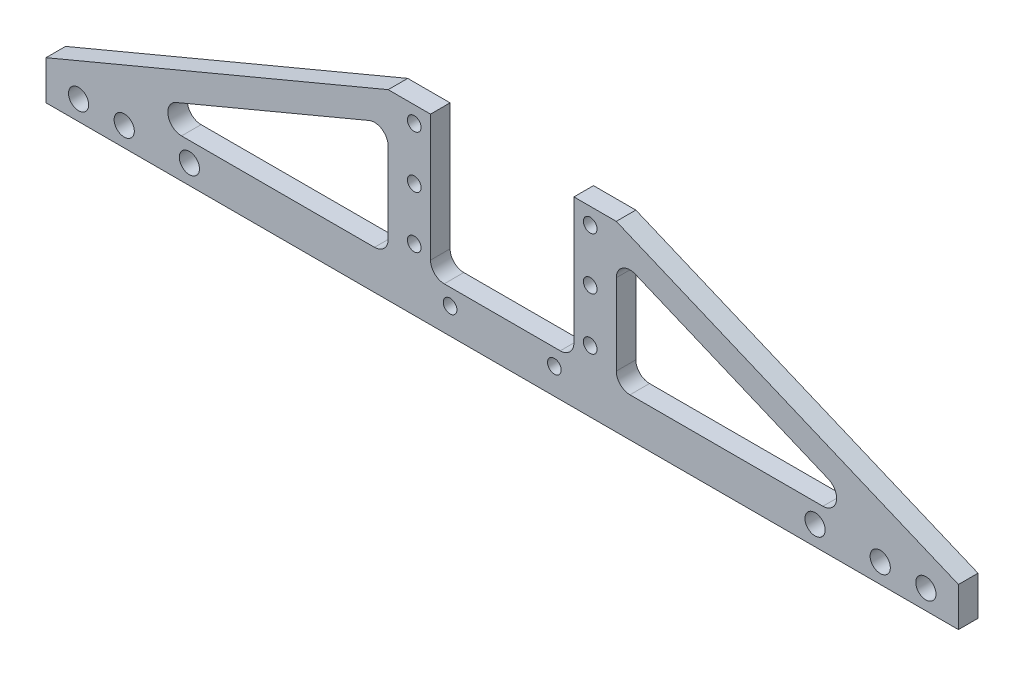
SolidWorks part; units mm, degrees
ref_plane "正面" through (0, 0, 0) normal (0, 0, 1) x (1, 0, 0)
ref_plane "平面" through (0, 0, 0) normal (0, 1, 0) x (1, 0, 0)
ref_plane "右側面" through (0, 0, 0) normal (1, 0, 0) x (0, 0, -1)
sketch "ｽｹｯﾁ1" plane through (0, 0, 0) normal (0, 0, 1) x (1, 0, 0)
  line L0 (-13.5, 21.5) -> (-13.5, 13.5) construction
  line L5 (-13.5, 13.5) -> (-13.5, 5.5) construction
  line L6 (-13.5, 5.5) -> (-13.5, 0) construction
  line L7 (-13.5, 0) -> (-8, 0) construction
  line L8 (-8, 0) -> (8, 0) construction
  line L9 (8, 0) -> (13.5, 0) construction
  line L10 (13.5, 0) -> (13.5, 5.5) construction
  line L11 (13.5, 5.5) -> (13.5, 13.5) construction
  line L12 (13.5, 13.5) -> (13.5, 21.5) construction
  line L13 (-11, 4.6) -> (-11, 24)
  line L14 (-11, 24) -> (-17.5, 24)
  line L15 (-17.5, 24) -> (-17.5, -4) construction
  line L16 (-17.5, -4) -> (17.5, -4)
  line L17 (17.5, -4) -> (17.5, 24) construction
  line L18 (17.5, 24) -> (11, 24)
  line L19 (11, 24) -> (11, 4.6)
  line L20 (8.9, 2.5) -> (-8.9, 2.5)
  line L21 (-17.5, 24) -> (-70, 2)
  line L22 (-70, -4) -> (-17.5, -4)
  line L23 (-17.5, 4.1) -> (-17.5, 16.5061)
  line L24 (-20.4116, 18.4429) -> (-50.017, 6.0368)
  line L25 (-49.2054, 2) -> (-19.6, 2)
  line L26 (-70, 2) -> (-70, -4)
  line L27 (-70, -1) -> (-65, -1) construction
  line L28 (-65, -1) -> (-65, -4) construction
  line L29 (0, -4) -> (0, 24) construction
  line L30 (70, -4) -> (17.5, -4)
  line L31 (70, 2) -> (70, -4)
  line L32 (17.5, 24) -> (70, 2)
  line L33 (20.4116, 18.4429) -> (50.017, 6.0368)
  line L34 (17.5, 4.1) -> (17.5, 16.5061)
  line L35 (49.2054, 2) -> (19.6, 2)
  circle A0 centre (-13.5, 5.5) radius 1.05
  circle A1 centre (-8, 0) radius 1.05
  circle A2 centre (8, 0) radius 1.05
  circle A3 centre (-13.5, 13.5) radius 1.05
  circle A4 centre (-13.5, 21.5) radius 1.05
  circle A5 centre (13.5, 21.5) radius 1.05
  circle A6 centre (13.5, 13.5) radius 1.05
  circle A7 centre (13.5, 5.5) radius 1.05
  arc A8 (-17.5, 4.1) -> (-19.6, 2) centre (-19.6, 4.1) cw
  arc A9 (-50.017, 6.0368) -> (-49.2054, 2) centre (-49.2054, 4.1) ccw
  arc A10 (-17.5, 16.5061) -> (-20.4116, 18.4429) centre (-19.6, 16.5061) ccw
  circle A11 centre (-65, -1) radius 1.55
  circle A12 centre (65, -1) radius 1.55
  arc A13 (17.5, 16.5061) -> (20.4116, 18.4429) centre (19.6, 16.5061) cw
  arc A14 (17.5, 4.1) -> (19.6, 2) centre (19.6, 4.1) ccw
  arc A15 (50.017, 6.0368) -> (49.2054, 2) centre (49.2054, 4.1) cw
  arc A16 (11, 4.6) -> (8.9, 2.5) centre (8.9, 4.6) cw
  arc A17 (-11, 4.6) -> (-8.9, 2.5) centre (-8.9, 4.6) ccw
  point P0 (0, 0)
  point P1 (0, 0)
  point P35 (-17.5, 2)
  point P40 (-17.5, 19.663)
  point P65 (0, 0)
  point P66 (0, 0)
  dimension "D3" = 2.1
  dimension "D15" = 2.1
  dimension "D17" = 3.1
  dimension "D19" = 2.1
  dimension "D1" = 5.5
  dimension "D2" = 8
  dimension "D4" = 27
  dimension "D5" = 2.5
  dimension "D6" = 2.5
  dimension "D7" = 2.5
  dimension "D8" = 4
  dimension "D9" = 4
  dimension "D10" = 2.5
  dimension "D11" = 4
  dimension "D12" = 70
  dimension "D13" = 4
  dimension "D14" = 6
  dimension "D16" = 6
  dimension "D18" = 5
extrude "ﾎﾞｽ - 押し出し1" add sketch "ｽｹｯﾁ1" along normal blind 3
sketch "ｽｹｯﾁ2" plane through (0, 0, 3) normal (0, 0, 1) x (1, 0, 0)
  line L0 (-70, -1) -> (-48, -1) construction
  line L1 (-70, 2) -> (-70, -4) construction
  line L2 (0, -4) -> (0, 2.5) construction
  line L3 (-70, -4) -> (70, -4) construction
  line L4 (8.9, 2.5) -> (-8.9, 2.5) construction
  circle A0 centre (-48, -1) radius 1.55
  circle A1 centre (48, -1) radius 1.55
  circle A2 centre (-58, -1) radius 1.55
  circle A3 centre (58, -1) radius 1.55
  dimension "D1" = 3.1
  dimension "D2" = 22
  dimension "D3" = 10
extrude "ｶｯﾄ - 押し出し1" cut sketch "ｽｹｯﾁ2" against normal blind 3
